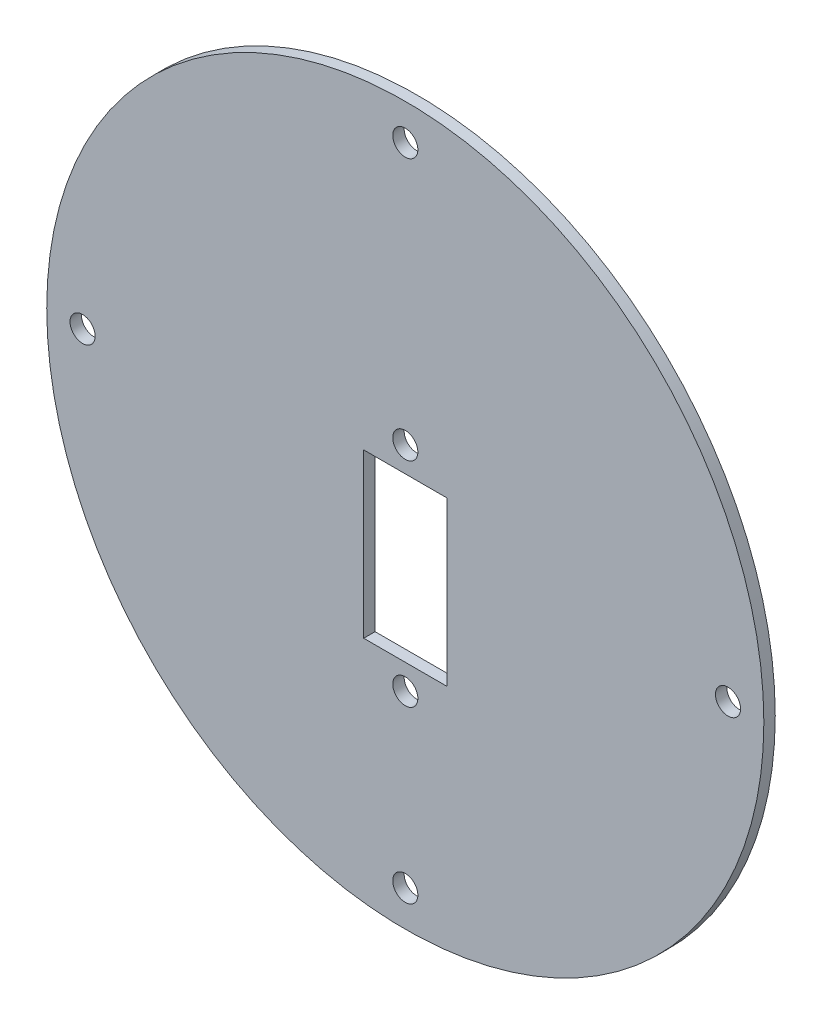
SolidWorks part; units mm, degrees
material "6061 Alloy"
ref_plane "Front Plane" through (0, 0, 0) normal (0, 0, 1) x (1, 0, 0)
ref_plane "Top Plane" through (0, 0, 0) normal (0, 1, 0) x (1, 0, 0)
ref_plane "Right Plane" through (0, 0, 0) normal (1, 0, 0) x (0, 0, -1)
sketch "Sketch1" plane through (0, 0, 0) normal (0, 0, 1) x (1, 0, 0)
  circle A0 centre (0, 0) radius 50
  dimension "D1" = 100
extrude "Boss-Extrude1" add sketch "Sketch1" along normal blind 1.59
sketch "Sketch2" plane through (0, 0, 1.59) normal (0, 0, 1) x (1, 0, 0)
  circle A0 centre (0, 0) radius 45 construction
  circle A1 centre (0, 45) radius 1.75
  circle A2 centre (45, 0) radius 1.75
  circle A3 centre (0, -45) radius 1.75
  circle A4 centre (-45, 0) radius 1.75
  point P14 (0, 0)
  dimension "D1" = 90
  dimension "D2" = 3.5
  dimension "D3" = 4
extrude "Cut-Extrude1" cut sketch "Sketch2" against normal blind 1.59
sketch "Sketch3" plane through (0, 0, 1.59) normal (0, 0, 1) x (1, 0, 0)
  line L1 (-5.8, 5) -> (5.8, 5)
  line L2 (-5.8, 5) -> (-5.8, -17.75)
  line L3 (-5.8, -17.75) -> (5.8, -17.75)
  line L4 (5.8, 5) -> (5.8, -17.75)
  line L5 (-5.8, 5) -> (5.8, -17.75) construction
  line L6 (-5.8, -17.75) -> (5.8, 5) construction
  circle A0 centre (0, 8.5) radius 1.75
  circle A1 centre (0, -21.25) radius 1.75
  point P0 (0, -6.375)
  dimension "D4" = 29.75
  dimension "D6" = 3.5
  dimension "D1" = 5
  dimension "D2" = 22.75
  dimension "D3" = 11.6
  dimension "D5" = 8.5
extrude "Cut-Extrude2" cut sketch "Sketch3" against normal blind 10
